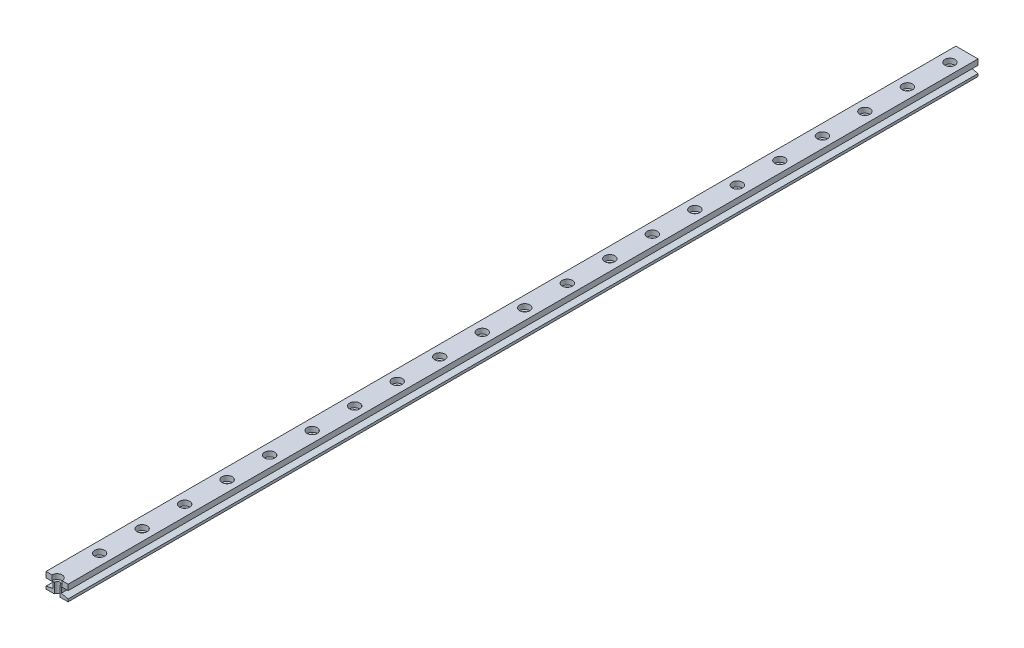
SolidWorks part; units mm, degrees
ref_plane "前视基准面" through (0, 0, 0) normal (0, 0, 1) x (1, 0, 0)
ref_plane "上视基准面" through (0, 0, 0) normal (0, 1, 0) x (1, 0, 0)
ref_plane "右视基准面" through (0, 0, 0) normal (1, 0, 0) x (0, 0, -1)
sketch "草图1" plane through (0, 0, 0) normal (0, 0, 1) x (1, 0, 0)
  line L0 (0, 6.4911) -> (0, -7.1696) construction
  line L1 (-6.5, 4.5) -> (6.5, 4.5)
  line L2 (-6.5, 4.5) -> (-6.5, 1.2)
  line L3 (-6.5, -4.5) -> (6.5, -4.5)
  line L4 (6.5, 4.5) -> (6.5, 1.2)
  line L5 (-6.5, 4.5) -> (6.5, -4.5) construction
  line L6 (-6.5, -4.5) -> (6.5, 4.5) construction
  line L7 (6.5, 1.2) -> (2.5, 1.2)
  line L8 (2.5, 1.2) -> (2.5, -2.0765)
  line L9 (2.5, -2.0765) -> (6.5, -3)
  line L10 (6.5, -3) -> (6.5, -4.5)
  line L11 (-2.5, -2.0765) -> (-6.5, -3)
  line L12 (-2.5, 1.2) -> (-2.5, -2.0765)
  line L13 (-6.5, 1.2) -> (-2.5, 1.2)
  line L14 (-6.5, -3) -> (-6.5, -4.5)
  point P0 (0, 0)
  dimension "D1" = 13
  dimension "D2" = 9
  dimension "D3" = 3.3
  dimension "D4" = 2.5
  dimension "D5" = 1.5
  dimension "D6" = 13
extrude "凸台-拉伸1" add sketch "草图1" along normal blind 800
sketch "草图2" plane through (0, 4.5, 0) normal (0, 1, 0) x (1, 0, 0)
  line L0 (0, -800) -> (0, -477.7695) construction
  line L1 (6.5, -800) -> (-6.5, -800) construction
  circle A0 centre (0, -790) radius 3
  dimension "D1" = 10
  dimension "D2" = 6
extrude "切除-拉伸1" cut sketch "草图2" against normal blind 3
sketch "草图3" plane through (0, 1.5, 0) normal (0, 1, 0) x (1, 0, 0)
  circle A0 centre (0, -790) radius 1.6
  dimension "D1" = 3.2
extrude "切除-拉伸2" cut sketch "草图3" against normal up to next
pattern_linear "阵列(线性)1" count 32 spacing 25 along (0, 0, -1) of "切除-拉伸2", "切除-拉伸1"
sketch "草图5" plane through (0, 4.5, 0) normal (0, 1, 0) x (1, 0, 0)
  line L0 (6.5, -800) -> (-6.5, -800) construction
  line L1 (-151.1129, -1193.0196) -> (151.1129, -1193.0196)
  line L2 (-151.1129, -1193.0196) -> (-151.1129, -690)
  line L3 (-151.1129, -690) -> (151.1129, -690)
  line L4 (151.1129, -1193.0196) -> (151.1129, -690)
  line L5 (-151.1129, -1193.0196) -> (151.1129, -690) construction
  line L6 (-151.1129, -690) -> (151.1129, -1193.0196) construction
  point P0 (0, -941.5098)
  dimension "D1" = 110
extrude "切除-拉伸3" cut sketch "草图5" against normal blind 10
sketch "草图6" plane through (0, 4.5, 0) normal (0, 1, 0) x (1, 0, 0)
  line L0 (0, 18.8804) -> (0, -157.7129) construction
  line L1 (6.5, 0) -> (-6.5, 0) construction
  line L2 (-13.7903, -155) -> (13.7903, -155)
  line L3 (-13.7903, -155) -> (-13.7903, 52.1933)
  line L4 (-13.7903, 52.1933) -> (13.7903, 52.1933)
  line L5 (13.7903, -155) -> (13.7903, 52.1933)
  line L6 (-13.7903, -155) -> (13.7903, 52.1933) construction
  line L7 (-13.7903, 52.1933) -> (13.7903, -155) construction
  point P4 (0, -51.4033)
  dimension "D1" = 155
extrude "切除-拉伸4" cut sketch "草图6" against normal blind 10
